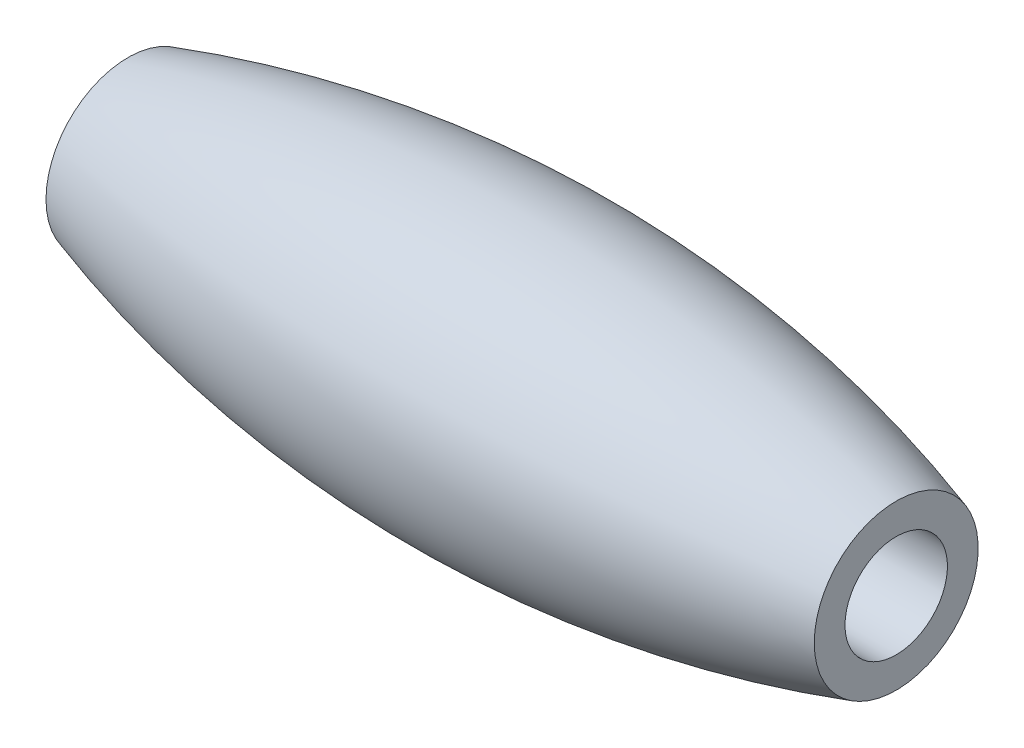
SolidWorks part; units mm, degrees
ref_plane "正面" through (0, 0, 0) normal (0, 0, 1) x (1, 0, 0)
ref_plane "平面" through (0, 0, 0) normal (0, 1, 0) x (1, 0, 0)
ref_plane "右側面" through (0, 0, 0) normal (1, 0, 0) x (0, 0, -1)
sketch "ｽｹｯﾁ1" plane through (0, 0, 0) normal (0, 0, 1) x (1, 0, 0)
  line L0 (-15, 0) -> (15, 0) construction
  line L1 (15, 0) -> (15, 2) construction
  line L2 (-15, 3.2) -> (-15, 2)
  line L3 (-15, 2) -> (-15, 0) construction
  line L4 (-15, 2) -> (15, 2)
  line L5 (15, 2) -> (15, 3.2)
  line L6 (0, 12.4) -> (0, 0) construction
  arc A1 (15, 3.2) -> (-15, 3.2) centre (0, -44.497) ccw
  point P10 (0, 0)
  dimension "D3" = 50
  dimension "D1" = 2
  dimension "D2" = 1.2
  dimension "D4" = 30
revolve "回転1" add sketch "ｽｹｯﾁ1" angle 360 about L0
